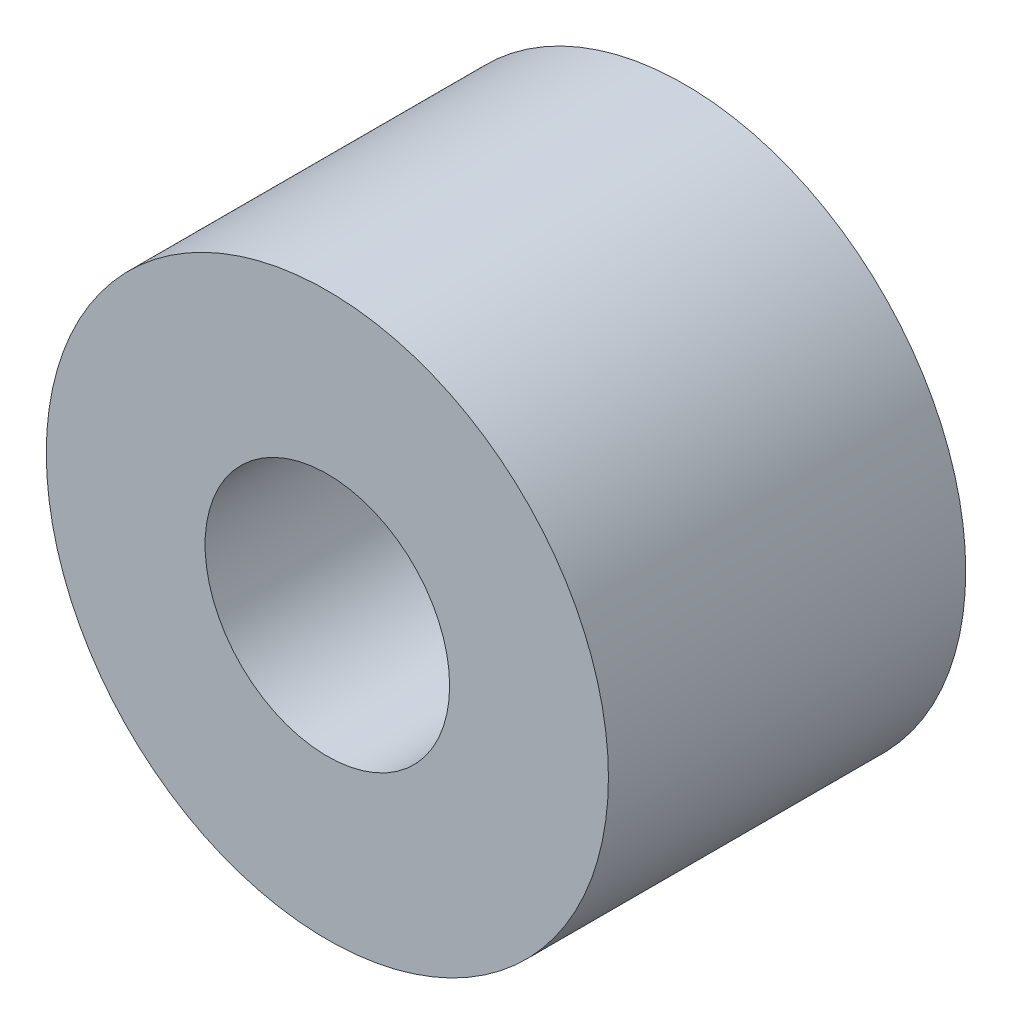
SolidWorks part; units mm, degrees
material "Delrin 2700 NC010, Low Viscosity Acetal Copolymer (SS)"
ref_plane "Front Plane" through (0, 0, 0) normal (0, 0, 1) x (1, 0, 0)
ref_plane "Top Plane" through (0, 0, 0) normal (0, 1, 0) x (1, 0, 0)
ref_plane "Right Plane" through (0, 0, 0) normal (1, 0, 0) x (0, 0, -1)
sketch "Sketch1" plane through (0, 0, 0) normal (0, 0, 1) x (1, 0, 0)
  circle A0 centre (0, 0) radius 4.8895
  circle A1 centre (0, 0) radius 11.2395
  dimension "D1" = 9.779
  dimension "D2" = 6.35
extrude "Boss-Extrude1" add sketch "Sketch1" along normal blind 14.2875
